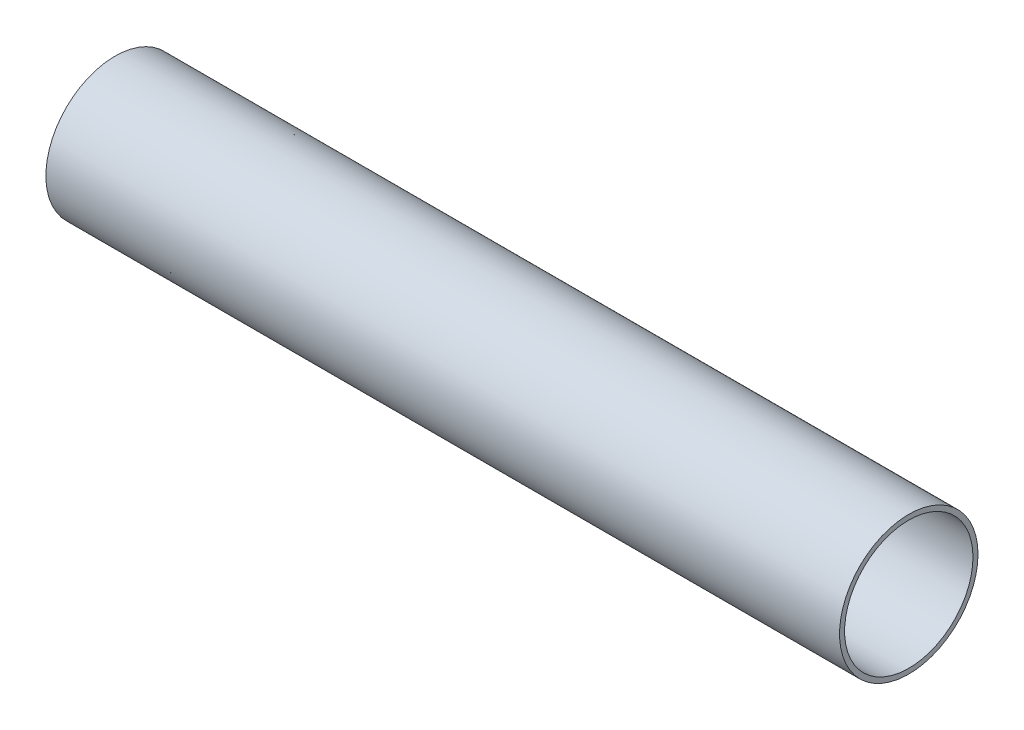
SolidWorks part; units mm, degrees
material "6061-T6 (SS)"
ref_plane "Front Plane" through (0, 0, 0) normal (0, 0, 1) x (1, 0, 0)
ref_plane "Top Plane" through (0, 0, 0) normal (0, 1, 0) x (1, 0, 0)
ref_plane "Right Plane" through (0, 0, 0) normal (1, 0, 0) x (0, 0, -1)
sketch "Sketch1" plane through (0, 0, 0) normal (1, 0, 0) x (0, 0, -1)
  circle A0 centre (0, 0) radius 37.6555
  circle A1 centre (0, 0) radius 34.925
  dimension "D1" = 69.85
  dimension "D2" = 75.311
extrude "Boss-Extrude1" add sketch "Sketch1" against normal blind 431.8
sketch "Sketch2" plane through (-431.8, 0, 0) normal (-1, 0, 0) x (0, 0, 1)
  circle A0 centre (0, 0) radius 35.7188
extrude "Cut-Extrude1" [suppressed] cut sketch "Sketch2" against normal blind 14.605
sketch "Sketch3" plane through (0, 0, 0) normal (0, 0, 1) x (1, 0, 0)
  line L0 (-431.8, 34.925) -> (-431.8, -34.925) construction
  line L1 (-431.8, 34.925) -> (-431.8, -34.925) construction
  line L2 (-431.8, 34.925) -> (-405.6126, 34.925) construction
  line L3 (0, -41.421) -> (0, 41.421) construction
  line L4 (-405.6126, 34.925) -> (-404.622, 34.925)
  line L5 (-405.6126, 34.925) -> (-405.6126, 35.8902)
  line L6 (-405.6126, 35.8902) -> (-404.622, 35.8902)
  line L7 (-404.622, 34.925) -> (-404.622, 35.8902)
  line L8 (-405.6126, 34.925) -> (-404.622, 35.8902) construction
  line L9 (-405.6126, 35.8902) -> (-404.622, 34.925) construction
  line L10 (-431.8, 0) -> (-363.1671, 0) construction
  point P6 (-405.1173, 35.4076)
  dimension "D1" = 404.622
  dimension "D2" = 0.9906
  dimension "D3" = 71.7804
revolve "Z-92479A230 Snap Ring Groove" cut sketch "Sketch3" angle 360 about L10
